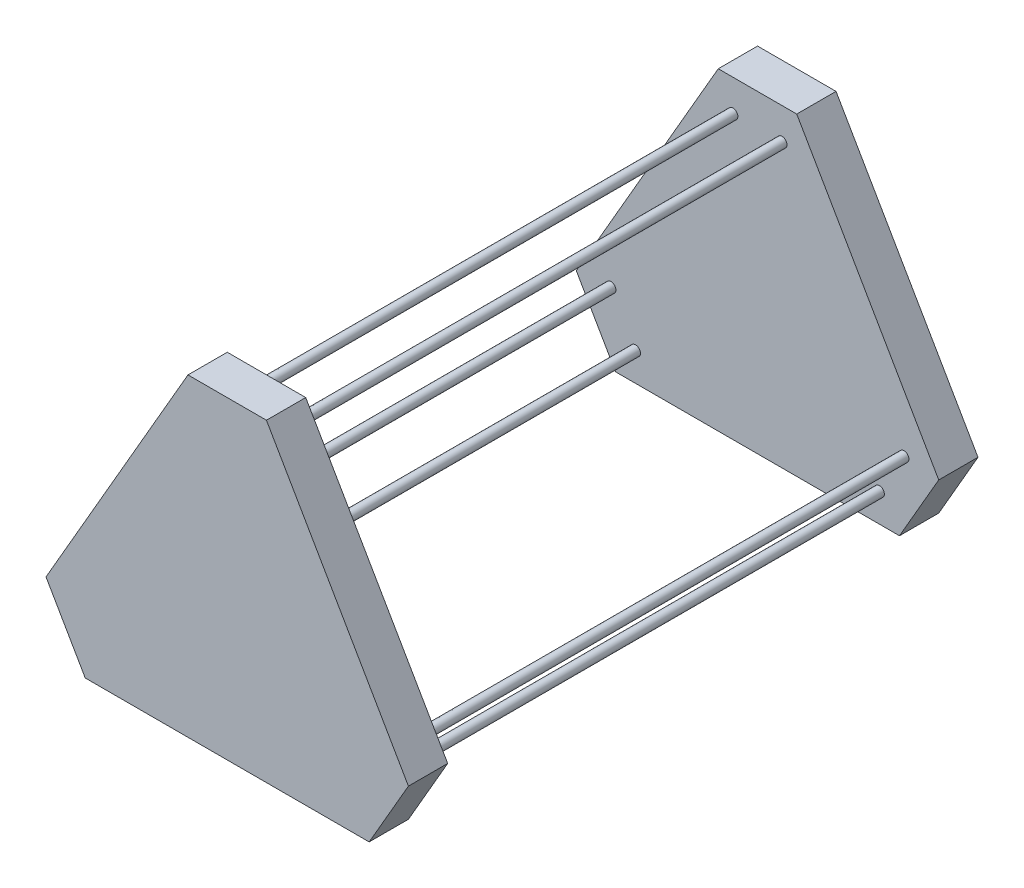
SolidWorks part; units mm, degrees
ref_plane "Front Plane" through (0, 0, 0) normal (0, 0, 1) x (1, 0, 0)
ref_plane "Top Plane" through (0, 0, 0) normal (0, 1, 0) x (1, 0, 0)
ref_plane "Right Plane" through (0, 0, 0) normal (1, 0, 0) x (0, 0, -1)
sketch "Sketch1" plane through (0, 0, 0) normal (0, 0, 1) x (1, 0, 0)
  line L0 (0, 0) -> (0, 129.5998) construction
  line L1 (184.521, -60.4002) -> (39.9524, 190)
  line L2 (-39.9524, 190) -> (-184.521, -60.4002)
  line L3 (-144.5686, -129.5998) -> (144.5686, -129.5998)
  line L4 (-39.9524, 190) -> (39.9524, 190)
  line L5 (184.521, -60.4002) -> (144.5686, -129.5998)
  line L6 (-144.5686, -129.5998) -> (-184.521, -60.4002)
  circle A0 centre (0, 0) radius 129.5998 construction
  point P15 (0, 0)
extrude "Boss-Extrude1" add sketch "Sketch1" against normal blind 40
sketch "Sketch2" plane through (0, 0, 0) normal (0, 0, 1) x (1, 0, 0)
  circle A0 centre (0, 0) radius 129.5998 construction
  circle A1 centre (0, 157.8411) radius 25 construction
  circle A2 centre (25, 157.8411) radius 5
  circle A3 centre (-25, 157.8411) radius 5
  circle A5 centre (124.1944, -100.5712) radius 5
  circle A6 centre (149.1944, -57.2699) radius 5
  circle A7 centre (-149.1944, -57.2699) radius 5
  circle A8 centre (-124.1944, -100.5712) radius 5
  point P20 (0, 0)
extrude "Boss-Extrude2" add sketch "Sketch2" along normal blind 500
ref_plane "Plane1" through (0, 0, 250) normal (0, 0, 1) x (1, 0, 0)
mirror "Mirror1" about plane through (0, 0, 250) normal (0, 0, 1) of "Boss-Extrude1"
